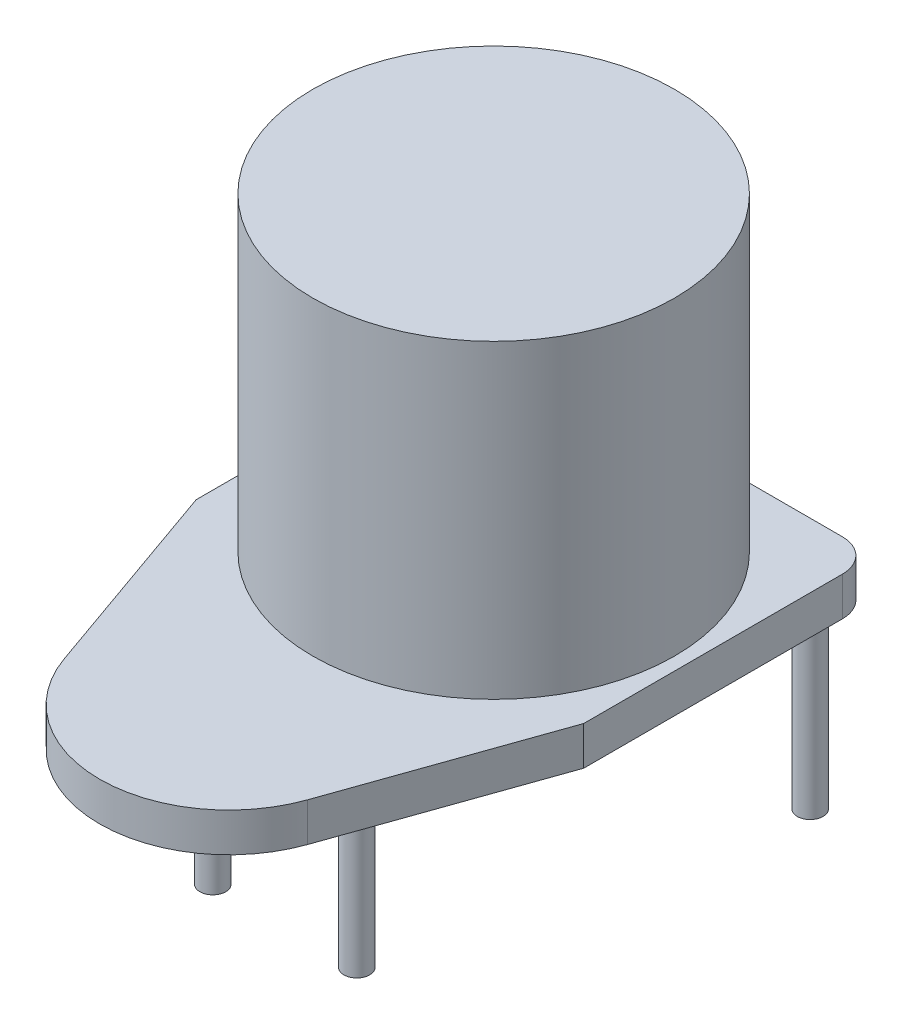
SolidWorks part; units mm, degrees
material "ABS"
ref_plane "Front Plane" through (0, 0, 0) normal (0, 0, 1) x (1, 0, 0)
ref_plane "Top Plane" through (0, 0, 0) normal (0, 1, 0) x (1, 0, 0)
ref_plane "Right Plane" through (0, 0, 0) normal (1, 0, 0) x (0, 0, -1)
sketch "Sketch1" plane through (0, 0, 0) normal (0, 1, 0) x (1, 0, 0)
  line L0 (-38.1, -0.4194) -> (-23.9551, -40.5447)
  line L2 (38.1, -0.4194) -> (38.1, 56.7998)
  line L3 (38.1, 56.7998) -> (-38.1, 56.7998)
  line L4 (-38.1, -0.4194) -> (-38.1, 56.7998)
  line L7 (38.1, -0.4194) -> (23.9551, -40.5447)
  arc A0 (-23.9551, -40.5447) -> (23.9551, -40.5447) centre (0, -32.1002) ccw
  point P0 (0, 0)
  dimension "D3" = 50.8
  dimension "D1" = 76.2
  dimension "D2" = 88.9
  dimension "D4" = 32.1002
  dimension "D5" = 57.2192
  dimension "D6" = 160.582
extrude "Boss-Extrude1" add sketch "Sketch1" along normal blind 7.62 from offset 38.1 contours A0 L7 L2 L3 L4 L0 | A0
fillet "Fillet1" radius 6.35 2 edges at (38.1, 41.91, -56.7998) (-38.1, 41.91, -56.7998)
sketch "Sketch3" plane through (0, 45.72, 0) normal (0, 1, 0) x (1, 0, 0)
  line L1 (38.1, -56.769) -> (-38.1, -56.769)
  line L2 (38.1, -56.769) -> (38.1, 56.769)
  line L3 (38.1, 56.769) -> (-38.1, 56.769)
  line L4 (-38.1, -56.769) -> (-38.1, 56.769)
  line L5 (38.1, -56.769) -> (-38.1, 56.769) construction
  line L6 (38.1, 56.769) -> (-38.1, -56.769) construction
  circle A1 centre (-31.75, 50.4498) radius 2.54
  circle A2 centre (31.75, 50.4498) radius 2.54
  circle A3 centre (-14.1546, -21.0904) radius 2.54
  circle A4 centre (14.1546, -21.0904) radius 2.54
  arc A5 (-31.75, 56.7998) -> (-38.1, 50.4498) centre (-31.75, 50.4498) ccw construction
  arc A6 (38.1, 50.4498) -> (31.75, 56.7998) centre (31.75, 50.4498) ccw construction
  point P0 (0, 0)
  dimension "D1" = 5.08
  dimension "D4" = 113.538
  dimension "D5" = 76.2
  dimension "D2" = 25.4
  dimension "D3" = 25.4
extrude "Boss-Extrude2" add sketch "Sketch3" against normal blind 43.18 contours A1 | A2 | A3 | A4
sketch "Sketch4" plane through (0, 45.72, 0) normal (0, 1, 0) x (1, 0, 0)
  line L0 (31.75, 56.7998) -> (-31.75, 56.7998) construction
  circle A0 centre (0, 19.9698) radius 35.56
  dimension "D1" = 71.12
  dimension "D2" = 36.83
extrude "Boss-Extrude3" add sketch "Sketch4" along normal blind 60.96
